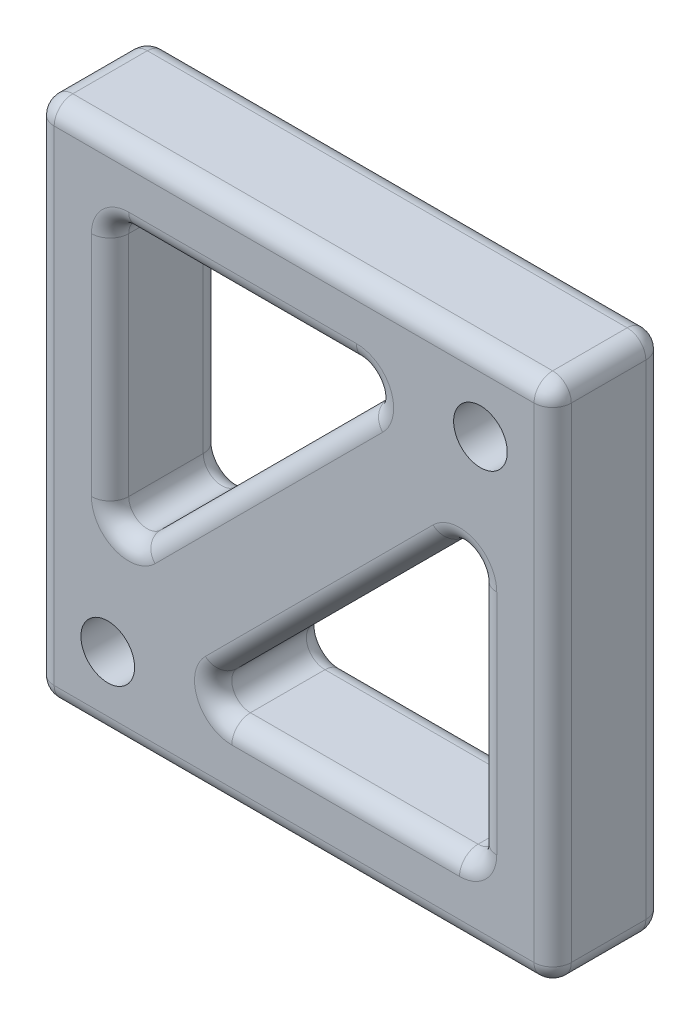
SolidWorks part; units mm, degrees
ref_plane "Front Plane" through (0, 0, 0) normal (0, 0, 1) x (1, 0, 0)
ref_plane "Top Plane" through (0, 0, 0) normal (0, 1, 0) x (1, 0, 0)
ref_plane "Right Plane" through (0, 0, 0) normal (1, 0, 0) x (0, 0, -1)
sketch "Sketch1" plane through (0, 0, 0) normal (0, 0, 1) x (1, 0, 0)
  line L1 (0, 0) -> (44.0553, 0)
  line L2 (0, 0) -> (0, 44.45)
  line L3 (0, 44.45) -> (44.0553, 44.45)
  line L4 (44.0553, 0) -> (44.0553, 44.45)
  point P5 (47.625, 44.45)
  point P7 (0, 44.45)
  point P8 (44.0553, 44.45)
  dimension "D1" = 44.45
  dimension "D2" = 44.0553
extrude "Boss-Extrude1" add sketch "Sketch1" along normal blind 9.525
sketch "Sketch2" plane through (0, 0, 0) normal (0, 0, -1) x (-1, 0, 0)
  circle A0 centre (-37.9026, 38.1) radius 2.286
  circle A1 centre (-6.1526, 6.35) radius 2.286
  dimension "D1" = 4.572
  dimension "D2" = 4.572
extrude "Cut-Extrude1" cut sketch "Sketch2" against normal through all
sketch "Sketch3" plane through (0, 0, 0) normal (0, 0, -1) x (-1, 0, 0)
  line L0 (-31.1674, 38.1) -> (-6.35, 38.1)
  line L1 (-6.35, 38.1) -> (-6.35, 13.2826)
  line L2 (-6.35, 13.2826) -> (-31.1674, 38.1)
  line L3 (-37.7053, 31.1674) -> (-12.8878, 6.35)
  line L4 (-12.8878, 6.35) -> (-37.7053, 6.35)
  line L5 (-37.7053, 6.35) -> (-37.7053, 31.1674)
  line L6 (-44.0553, 44.45) -> (0, 44.45) construction
  line L7 (0, 44.45) -> (0, 0) construction
  line L8 (0, 0) -> (-44.0553, 0) construction
  line L9 (-44.0553, 0) -> (-44.0553, 44.45) construction
  point P14 (-37.7053, 30.4843)
  point P15 (-32.4045, 38.1)
  point P16 (-10.8977, 6.35)
  point P17 (-11.5229, 6.35)
  point P18 (-11.7729, 6.35)
  point P19 (-14.6881, 6.35)
  dimension "D1" = 6.35
  dimension "D2" = 6.35
  dimension "D3" = 6.35
  dimension "D4" = 6.35
  dimension "D5" = 9.525
extrude "Cut-Extrude2" cut sketch "Sketch3" against normal through all
fillet "Fillet1" radius 1.5875 30 edges at (18.7587, 25.6913, 9.525) (18.7587, 25.6913, 0) (18.7587, 38.1, 9.525) (18.7587, 38.1, 0) (25.2965, 18.7587, 9.525) (25.2965, 18.7587, 0) (37.7053, 31.1674, 4.7625) (37.7053, 18.7587, 9.525) (37.7053, 18.7587, 0) (22.0276, 0, 9.525) (22.0276, 0, 0) (22.0276, 44.45, 9.525) (22.0276, 44.45, 0) (44.0553, 0, 4.7625) (44.0553, 22.225, 9.525) (44.0553, 44.45, 4.7625) (44.0553, 22.225, 0) (0, 44.45, 4.7625) (0, 22.225, 9.525) (0, 0, 4.7625) (0, 22.225, 0) (6.35, 13.2826, 4.7625) (6.35, 25.6913, 9.525) (6.35, 38.1, 4.7625) (6.35, 25.6913, 0) (37.7053, 6.35, 4.7625) (25.2965, 6.35, 9.525) (12.8878, 6.35, 4.7625) (25.2965, 6.35, 0) (31.1674, 38.1, 4.7625)
